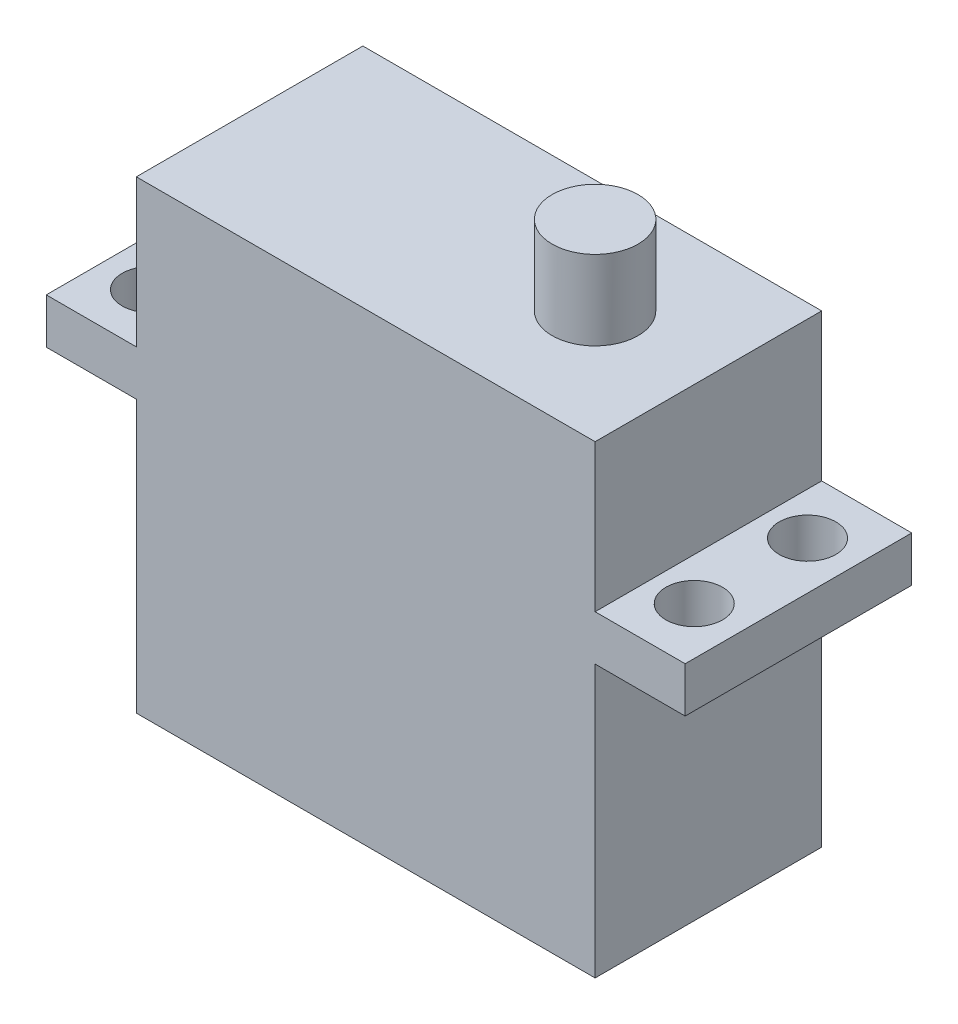
SolidWorks part; units mm, degrees
ref_plane "Front Plane" through (0, 0, 0) normal (0, 0, 1) x (1, 0, 0)
ref_plane "Top Plane" through (0, 0, 0) normal (0, 1, 0) x (1, 0, 0)
ref_plane "Right Plane" through (0, 0, 0) normal (1, 0, 0) x (0, 0, -1)
sketch "Sketch2" plane through (0, 0, 0) normal (0, 0, 1) x (1, 0, 0)
  line L1 (-20.25, 20.5) -> (20.25, 20.5)
  line L2 (-20.25, 20.5) -> (-20.25, -20.5)
  line L3 (-20.25, -20.5) -> (20.25, -20.5)
  line L4 (20.25, 20.5) -> (20.25, -20.5)
  line L5 (-20.25, 20.5) -> (20.25, -20.5) construction
  line L6 (-20.25, -20.5) -> (20.25, 20.5) construction
  point P0 (0, 0)
  dimension "D1" = 41
  dimension "D2" = 40.5
extrude "Boss-Extrude1" add sketch "Sketch2" along normal blind 20
sketch "Sketch4" plane through (20.25, 0, 0) normal (1, 0, 0) x (0, 0, -1)
  line L0 (-20, -20.5) -> (-20, 20.5) construction
  line L1 (-20, 7.5) -> (0, 7.5)
  line L2 (-20, 7.5) -> (-20, 3.5)
  line L3 (-20, 3.5) -> (0, 3.5)
  line L4 (0, 7.5) -> (0, 3.5)
  line L5 (-20, -20.5) -> (0, -20.5) construction
  dimension "D1" = 4
  dimension "D2" = 28
extrude "Boss-Extrude2" add sketch "Sketch4" along normal blind 7.95
sketch "Sketch5" plane through (-20.25, 0, 0) normal (-1, 0, 0) x (0, 0, 1)
  line L0 (0, 20.5) -> (0, -20.5) construction
  line L1 (0, 7.5) -> (20, 7.5)
  line L2 (0, 7.5) -> (0, 3.5)
  line L3 (0, 3.5) -> (20, 3.5)
  line L4 (20, 7.5) -> (20, 3.5)
  line L5 (20, 20.5) -> (20, -20.5) construction
  line L6 (20, -20.5) -> (0, -20.5) construction
  dimension "D1" = 4
  dimension "D2" = 28
extrude "Boss-Extrude3" add sketch "Sketch5" along normal blind 7.95
sketch "Sketch8" plane through (0, 7.5, 0) normal (0, 1, 0) x (1, 0, 0)
  line L0 (-28.2, 0) -> (-20.25, 0) construction
  line L1 (28.2, 0) -> (20.25, 0) construction
  circle A0 centre (24, -5) radius 2.5
  circle A1 centre (24, -15) radius 2.5
  circle A2 centre (-24, -5) radius 2.5
  circle A3 centre (-24, -15) radius 2.5
  dimension "D1" = 5
  dimension "D2" = 5
  dimension "D4" = 5
  dimension "D5" = 5
  dimension "D3" = 10
  dimension "D6" = 10
  dimension "D7" = 24
  dimension "D8" = 24
  dimension "D9" = 24
  dimension "D10" = 24
  dimension "D11" = 5
  dimension "D12" = 5
extrude "Cut-Extrude1" cut sketch "Sketch8" against normal through all
sketch "Sketch11" plane through (0, 20.5, 0) normal (0, 1, 0) x (1, 0, 0)
  line L0 (20.25, 0) -> (20.25, -20) construction
  circle A0 centre (10.25, -10) radius 3.7925
  point P5 (20.25, -10)
  dimension "D1" = 10
  dimension "D2" = 10
extrude "Boss-Extrude4" add sketch "Sketch11" along normal blind 7
